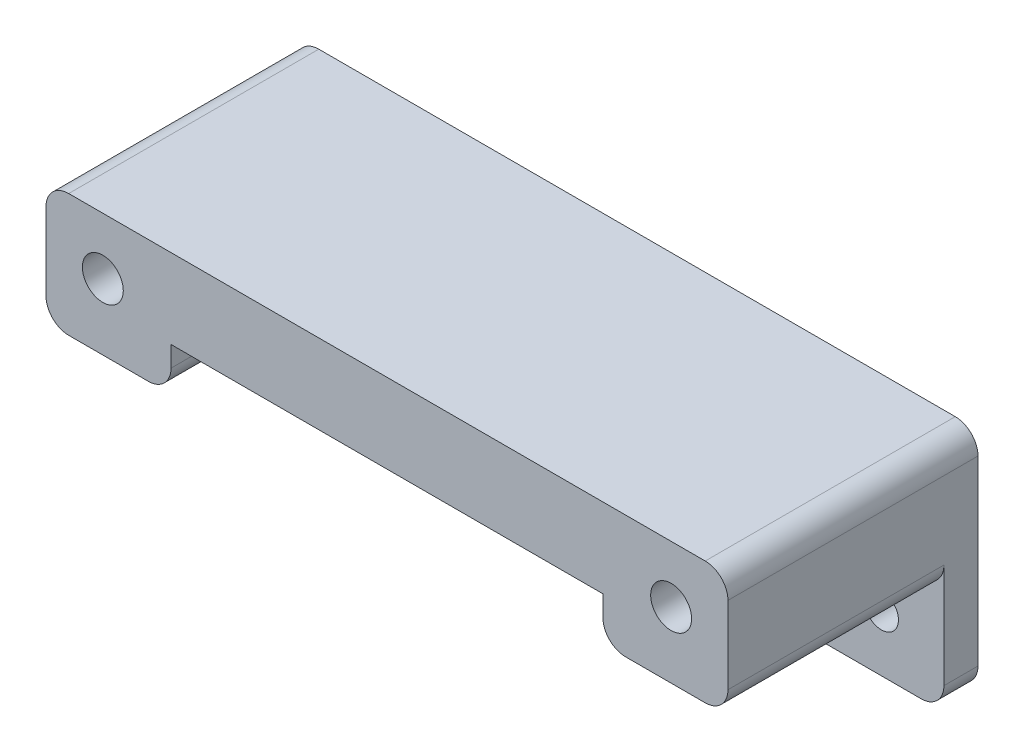
SolidWorks part; units mm, degrees
ref_plane "正面" through (0, 0, 0) normal (0, 0, 1) x (1, 0, 0)
ref_plane "平面" through (0, 0, 0) normal (0, 1, 0) x (1, 0, 0)
ref_plane "右側面" through (0, 0, 0) normal (1, 0, 0) x (0, 0, -1)
sketch "ｽｹｯﾁ1" plane through (0, 0, 0) normal (0, 0, 1) x (1, 0, 0)
  line L0 (6.4904, -9.6635) -> (6.4904, -29.6635) construction
  line L1 (-23.5096, -9.6635) -> (36.4904, -9.6635)
  line L2 (-23.5096, -9.6635) -> (-23.5096, -29.6635)
  line L3 (-23.5096, -29.6635) -> (36.4904, -29.6635)
  line L4 (36.4904, -9.6635) -> (36.4904, -29.6635)
  line L5 (-23.5096, -24.6635) -> (36.4904, -24.6635) construction
  circle A0 centre (30.9904, -24.6635) radius 1.5
  circle A1 centre (-18.0096, -24.6635) radius 1.5
  dimension "D6" = 3
  dimension "D1" = 60
  dimension "D2" = 20
  dimension "D3" = 5
  dimension "D4" = 24.5
  dimension "D5" = 24.5
extrude "ﾎﾞｽ - 押し出し2" add sketch "ｽｹｯﾁ1" along normal blind 3
sketch "ｽｹｯﾁ2" plane through (0, 0, 3) normal (0, 0, 1) x (1, 0, 0)
  line L0 (6.4904, -9.6635) -> (6.4904, -29.6635) construction
  line L1 (36.4904, -9.6635) -> (-23.5096, -9.6635) construction
  line L2 (-23.5096, -29.6635) -> (36.4904, -29.6635) construction
  line L3 (6.4904, -16.6635) -> (25.4904, -16.6635)
  line L4 (-18.0096, -24.6635) -> (30.9904, -24.6635) construction
  line L5 (6.4904, -16.6635) -> (-12.5096, -16.6635)
  line L6 (-12.5096, -20.4705) -> (-23.5096, -20.4705)
  line L7 (-23.5096, -9.6635) -> (-23.5096, -29.6635) construction
  line L8 (-23.5096, -20.4705) -> (-23.5096, -9.6635)
  line L9 (-23.5096, -9.6635) -> (36.4904, -9.6635)
  line L10 (36.4904, -9.6635) -> (36.4904, -20.4705)
  line L11 (36.4904, -29.6635) -> (36.4904, -9.6635) construction
  line L12 (36.4904, -20.4705) -> (25.4904, -20.4705)
  line L13 (25.4904, -20.4705) -> (25.4904, -16.6635)
  line L14 (-12.5096, -16.6635) -> (-12.5096, -20.4705)
  dimension "D1" = 8
  dimension "D2" = 19
extrude "ﾎﾞｽ - 押し出し3" add sketch "ｽｹｯﾁ2" along normal blind 19
sketch "ｽｹｯﾁ3" plane through (0, 0, 22) normal (0, 0, 1) x (1, 0, 0)
  line L0 (-23.5096, -14.6635) -> (36.4904, -14.6635) construction
  line L1 (-23.5096, -9.6635) -> (-23.5096, -20.4705) construction
  line L2 (36.4904, -20.4705) -> (36.4904, -9.6635) construction
  line L3 (6.4904, -9.6635) -> (6.4904, -30.8001) construction
  line L4 (36.4904, -9.6635) -> (-23.5096, -9.6635) construction
  line L5 (-18.0096, -24.6635) -> (30.9904, -24.6635) construction
  line L6 (-12.5096, -16.6635) -> (25.4904, -16.6635) construction
  circle A0 centre (31.4904, -14.6635) radius 1.8
  circle A1 centre (-18.5096, -14.6635) radius 1.8
  dimension "D1" = 3.6
  dimension "D2" = 25
  dimension "D3" = 25
  dimension "D4" = 10
  dimension "D5" = 8
extrude "ｶｯﾄ - 押し出し1" cut sketch "ｽｹｯﾁ3" against normal through all
fillet "ﾌｨﾚｯﾄ1" radius 2 8 edges at (-12.5096, -20.4705, 12.5) (25.4904, -20.4705, 12.5) (-23.5096, -29.6635, 1.5) (36.4904, -29.6635, 1.5) (-23.5096, -20.4705, 12.5) (36.4904, -20.4705, 12.5) (-23.5096, -9.6635, 11) (36.4904, -9.6635, 11)
